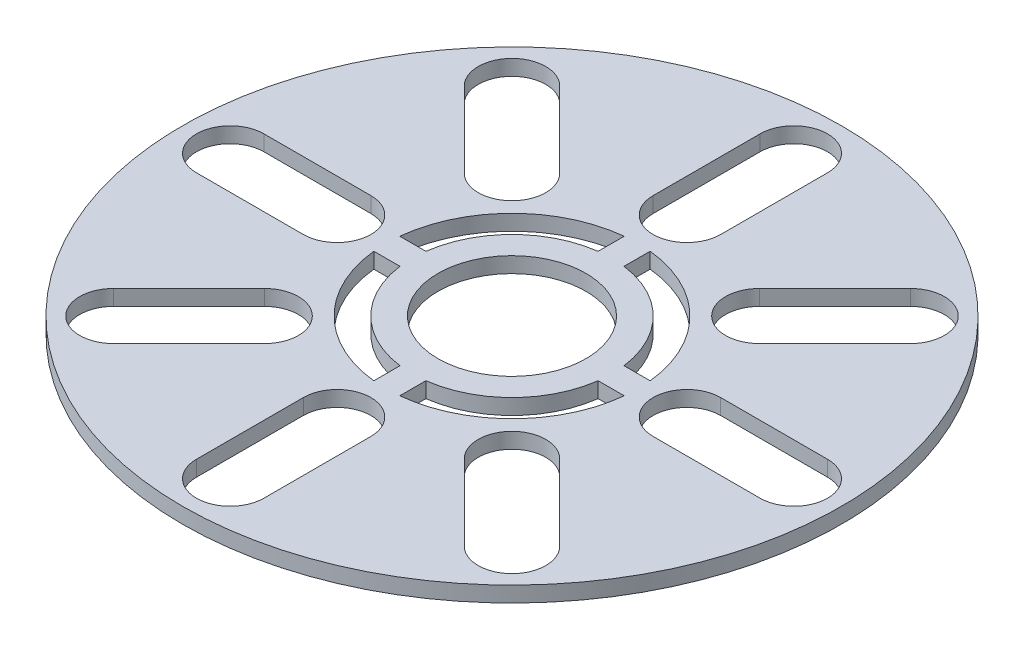
SolidWorks part; units mm, degrees
ref_plane "Front Plane" through (0, 0, 0) normal (0, 0, 1) x (1, 0, 0)
ref_plane "Top Plane" through (0, 0, 0) normal (0, 1, 0) x (1, 0, 0)
ref_plane "Right Plane" through (0, 0, 0) normal (1, 0, 0) x (0, 0, -1)
sketch "Sketch1" plane through (0, 0, 0) normal (0, 1, 0) x (1, 0, 0)
  line L0 (-2.5, 19.087) -> (-2.5, 24.1208)
  line L1 (2.5, 19.087) -> (2.5, 24.1208)
  line L2 (19.087, 2.5) -> (24.1208, 2.5)
  line L3 (19.087, -2.5) -> (24.1208, -2.5)
  line L4 (2.5, -19.087) -> (2.5, -24.1208)
  line L5 (-2.5, -19.087) -> (-2.5, -24.1208)
  line L6 (-19.087, -2.5) -> (-24.1208, -2.5)
  line L7 (-19.087, 2.5) -> (-24.1208, 2.5)
  circle A1 centre (0, 0) radius 14.25
  arc A2 (-2.5, 24.1208) -> (-24.1208, 2.5) centre (0, 0) ccw
  arc A3 (-2.5, 19.087) -> (-19.087, 2.5) centre (0, 0) ccw
  circle A4 centre (0, 0) radius 63.5
  arc A5 (19.087, 2.5) -> (2.5, 19.087) centre (0, 0) ccw
  arc A6 (24.1208, 2.5) -> (2.5, 24.1208) centre (0, 0) ccw
  arc A7 (2.5, -19.087) -> (19.087, -2.5) centre (0, 0) ccw
  arc A8 (2.5, -24.1208) -> (24.1208, -2.5) centre (0, 0) ccw
  arc A9 (-24.1208, -2.5) -> (-2.5, -24.1208) centre (0, 0) ccw
  arc A10 (-19.087, -2.5) -> (-2.5, -19.087) centre (0, 0) ccw
  point P25 (0, 0)
  point P94 (0, 0)
  dimension "D1" = 127
  dimension "D2" = 28.5
  dimension "D3" = 48.5
  dimension "D4" = 38.5
  dimension "D5" = 5
  dimension "D6" = 2.5
  dimension "D7" = 4
extrude "Boss-Extrude1" add sketch "Sketch1" along normal blind 3
sketch "Sketch3" plane through (0, 3, 0) normal (0, 1, 0) x (1, 0, 0)
  circle A0 centre (0, 0) radius 20.75
  dimension "D1" = 41.5
sketch "Sketch4" plane through (0, 3, 0) normal (0, 1, 0) x (1, 0, 0)
  line L0 (0, 33.7) -> (0, 54.3) construction
  line L1 (-6.5, 33.7) -> (-6.5, 54.3)
  line L2 (6.5, 33.7) -> (6.5, 54.3)
  arc A0 (-6.5, 33.7) -> (6.5, 33.7) centre (0, 33.7) ccw
  arc A1 (6.5, 54.3) -> (-6.5, 54.3) centre (0, 54.3) ccw
  point P3 (0, 44)
  dimension "D1" = 6.5
  dimension "D2" = 44
  dimension "D3" = 20.6
extrude "Cut-Extrude1" cut sketch "Sketch4" against normal through all
pattern_circular "CirPattern1" count 8 over 360 about axis through (0, 0, 0) along (0, 1, 0) of "Cut-Extrude1"
